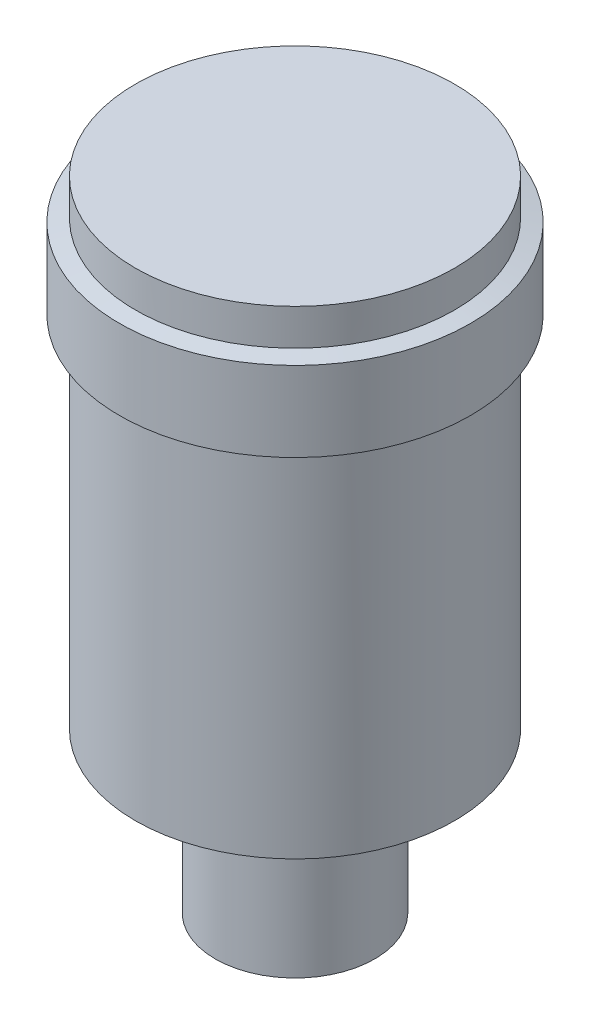
SolidWorks part; units mm, degrees
ref_plane "前视基准面" through (0, 0, 0) normal (0, 0, 1) x (1, 0, 0)
ref_plane "上视基准面" through (0, 0, 0) normal (0, 1, 0) x (1, 0, 0)
ref_plane "右视基准面" through (0, 0, 0) normal (1, 0, 0) x (0, 0, -1)
other "Configuration Table"
sketch "草图1" plane through (0, 0, 0) normal (0, 1, 0) x (1, 0, 0)
  circle A0 centre (0, 0) radius 1
  dimension "D1" = 2
extrude "凸台-拉伸1" add sketch "草图1" along normal blind 2
sketch "草图2" plane through (0, 2, 0) normal (0, 1, 0) x (1, 0, 0)
  circle A0 centre (0, 0) radius 2
  dimension "D1" = 4
extrude "凸台-拉伸2" add sketch "草图2" along normal blind 6
sketch "草图3" plane through (0, 0, 0) normal (0, 0, 1) x (1, 0, 0)
  line L0 (0, 8) -> (0, 6)
  line L1 (2, 8) -> (-2, 8) construction
  line L2 (0, 7) -> (2.2, 7) construction
  line L3 (2.2, 7.5) -> (2.2, 6.5)
  line L4 (2.2, 7.5) -> (0, 8)
  line L5 (2.2, 6.5) -> (0, 6)
  line L6 (0, 7) -> (0, 0) construction
  point P10 (2.2, 7)
  dimension "D1" = 2
  dimension "D2" = 2.2
  dimension "D3" = 0.5
revolve "旋转1" add sketch "草图3" angle 360 about L0
